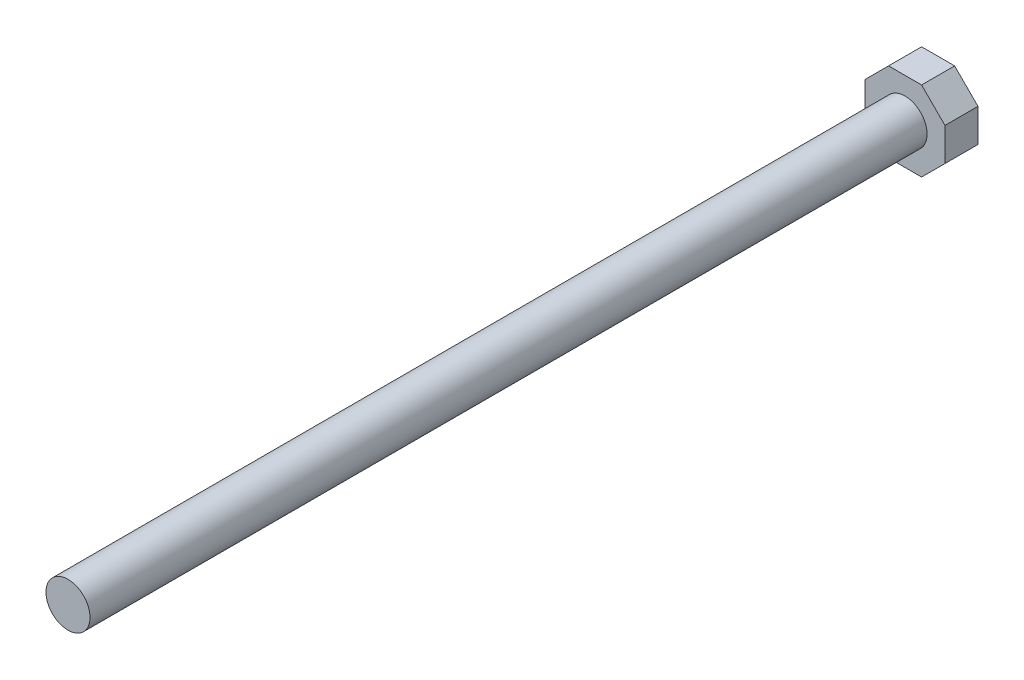
SolidWorks part; units mm, degrees
ref_plane "Ebene vorne" through (0, 0, 0) normal (0, 0, 1) x (1, 0, 0)
ref_plane "Ebene oben" through (0, 0, 0) normal (0, 1, 0) x (1, 0, 0)
ref_plane "Ebene rechts" through (0, 0, 0) normal (1, 0, 0) x (0, 0, -1)
sketch "Skizze1" plane through (0, 0, 0) normal (0, 0, 1) x (1, 0, 0)
  line L0 (-1.777, 0.2852) -> (0.3443, 2.4065)
  line L1 (0.3443, 2.4065) -> (3.3443, 2.4065)
  line L2 (3.3443, 2.4065) -> (5.4656, 0.2852)
  line L3 (5.4656, 0.2852) -> (5.4656, -2.7148)
  line L4 (5.4656, -2.7148) -> (3.3443, -4.8361)
  line L5 (3.3443, -4.8361) -> (0.3443, -4.8361)
  line L6 (0.3443, -4.8361) -> (-1.777, -2.7148)
  line L7 (-1.777, -2.7148) -> (-1.777, 0.2852)
  dimension "D1" = 3
  dimension "D2" = 3
  dimension "D3" = 3
  dimension "D4" = 3
extrude "Aufsatz-Linear austragen1" add sketch "Skizze1" along normal blind 3
sketch "Skizze2" plane through (0, 0, 3) normal (0, 0, 1) x (1, 0, 0)
  line L0 (-1.777, -2.7148) -> (5.4656, 0.2852) construction
  line L1 (0.3443, 2.4065) -> (3.3443, -4.8361) construction
  circle A0 centre (1.8443, -1.2148) radius 2
extrude "Aufsatz-Linear austragen2" add sketch "Skizze2" along normal blind 76
